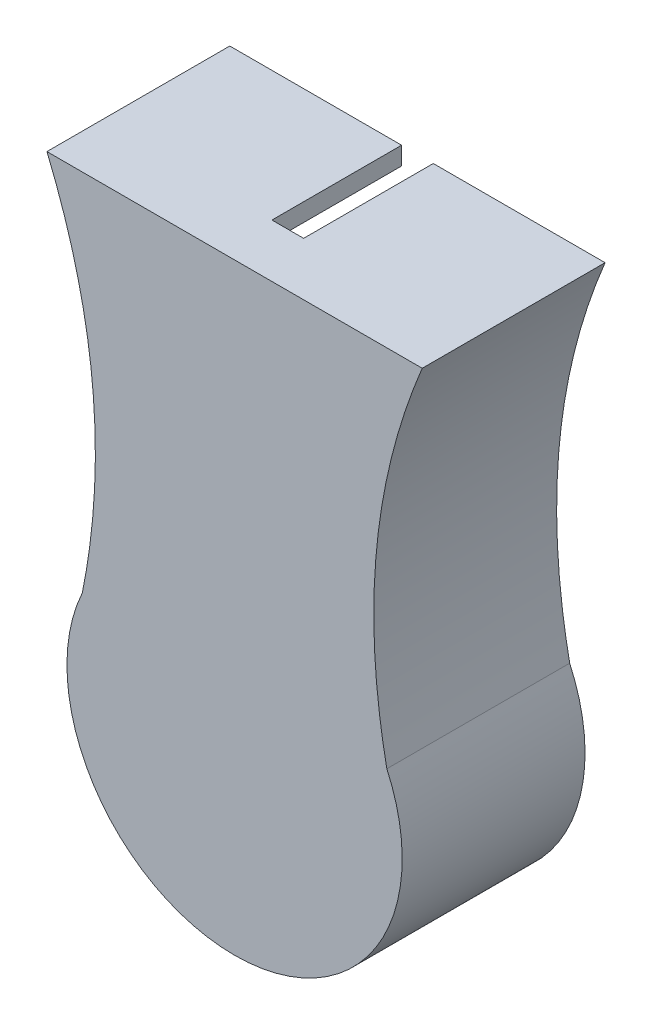
SolidWorks part; units mm, degrees
ref_plane "Front Plane" through (0, 0, 0) normal (0, 0, 1) x (1, 0, 0)
ref_plane "Top Plane" through (0, 0, 0) normal (0, 1, 0) x (1, 0, 0)
ref_plane "Right Plane" through (0, 0, 0) normal (1, 0, 0) x (0, 0, -1)
sketch "Sketch1" plane through (0, 0, 0) normal (0, 0, 1) x (1, 0, 0)
  line L0 (-40.1725, 37.9216) -> (0, 0) construction
  line L1 (0, 0) -> (0, 104.627) construction
  line L2 (0, 0) -> (42.2445, 37.9216) construction
  line L3 (-30.7873, 71.3076) -> (30.7873, 71.3076)
  circle A1 centre (0, 0) radius 27.5
  spline S0 degree 2 poles (-30.7873, 71.3076) (-18.7115, 42.3682) (-24.983, 11.4935) knots 0 0 0 1 1 1
  spline S1 degree 2 poles (30.7873, 71.3076) (18.7115, 42.3682) (24.983, 11.4935) knots 0 0 0 1 1 1
  point P12 (23.4698, 43.5104)
  dimension "D1" = 55
extrude "Boss-Extrude1" add sketch "Sketch1" along normal blind 30 contours S1 L3 S0 A1 | S1 A1 S0
sketch "Sketch2" plane through (0, 0, 0) normal (0, 0, 1) x (1, 0, 0)
  line L0 (0, 0) -> (0, 97.3244) construction
  line L2 (21.25, 66.25) -> (-21.25, 66.25)
  line L3 (21.25, 66.25) -> (21.25, 23.75)
  line L4 (21.25, 23.75) -> (-21.25, 23.75)
  line L5 (-21.25, 66.25) -> (-21.25, 23.75)
  line L6 (21.25, 66.25) -> (-21.25, 23.75) construction
  line L7 (21.25, 23.75) -> (-21.25, 66.25) construction
  line L8 (-30.7873, 71.3076) -> (30.7873, 71.3076) construction
  line L9 (11.6, 66.25) -> (-11.6, 66.25)
  line L10 (11.6, 66.25) -> (11.6, 68.35)
  line L11 (11.6, 68.35) -> (-11.6, 68.35)
  line L12 (-11.6, 66.25) -> (-11.6, 68.35)
  line L13 (2.6, 68.35) -> (-2.6, 68.35)
  line L14 (2.6, 68.35) -> (2.6, 71.3076)
  line L15 (2.6, 71.3076) -> (-2.6, 71.3076)
  line L16 (-2.6, 68.35) -> (-2.6, 71.3076)
  point P3 (0, 45)
  dimension "D1" = 42.5
  dimension "D2" = 42.5
  dimension "D3" = 45
  dimension "D4" = 23.2
  dimension "D5" = 2.1
  dimension "D6" = 5.2
extrude "Cut-Extrude1" cut sketch "Sketch2" along normal blind 21.27 contours L2 L5 L4 L3 | L12 L2 L10 L11 | L16 L15 L14 L13
